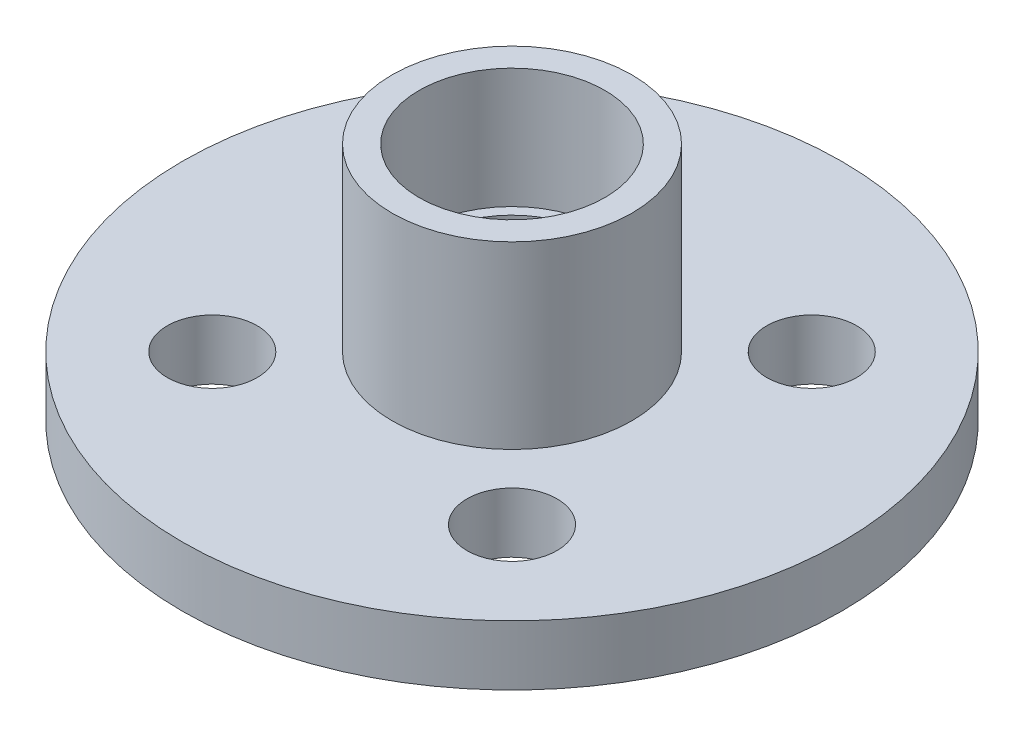
SolidWorks part; units mm, degrees
ref_plane "前视基准面" through (0, 0, 0) normal (0, 0, 1) x (1, 0, 0)
ref_plane "上视基准面" through (0, 0, 0) normal (0, 1, 0) x (1, 0, 0)
ref_plane "右视基准面" through (0, 0, 0) normal (1, 0, 0) x (0, 0, -1)
other "Configuration Table"
sketch "草图1" plane through (0, 0, 0) normal (0, 1, 0) x (1, 0, 0)
  line L1 (-5, -5) -> (5, -5)
  line L2 (-5, -5) -> (-5, 5)
  line L3 (-5, 5) -> (5, 5)
  line L4 (5, -5) -> (5, 5)
  line L5 (-5, -5) -> (5, 5) construction
  line L6 (-5, 5) -> (5, -5) construction
  circle A0 centre (0, 0) radius 1.5
  circle A1 centre (-5, 5) radius 1.5
  circle A2 centre (5, 5) radius 1.5
  circle A3 centre (5, -5) radius 1.5
  circle A4 centre (-5, -5) radius 1.5
  circle A5 centre (0, 0) radius 11
  dimension "D1" = 3
  dimension "D4" = 3
  dimension "D6" = 22
  dimension "D2" = 10
  dimension "D3" = 10
  dimension "D5" = 4
extrude "凸台-拉伸4" add sketch "草图1" along normal blind 2 contours A4 L1 A3 L4 A2 L3 A1 L2 A0 | A5 A4 L2 A1 L3 A2 L4 A3 L1
sketch "草图2" plane through (0, 2, 0) normal (0, 1, 0) x (1, 0, 0)
  circle A1 centre (0, 0) radius 4
  dimension "D2" = 8
extrude "凸台-拉伸5" add sketch "草图2" along normal blind 6
sketch "草图3" plane through (0, 8, 0) normal (0, 1, 0) x (1, 0, 0)
  circle A0 centre (0, 0) radius 3.1
  dimension "D1" = 6.2
extrude "切除-拉伸1" cut sketch "草图3" against normal blind 4
sketch "草图4" plane through (0, 4, 0) normal (0, 1, 0) x (1, 0, 0)
  circle A0 centre (0, 0) radius 2.75
  dimension "D1" = 5.5
extrude "切除-拉伸2" cut sketch "草图4" against normal blind 3
